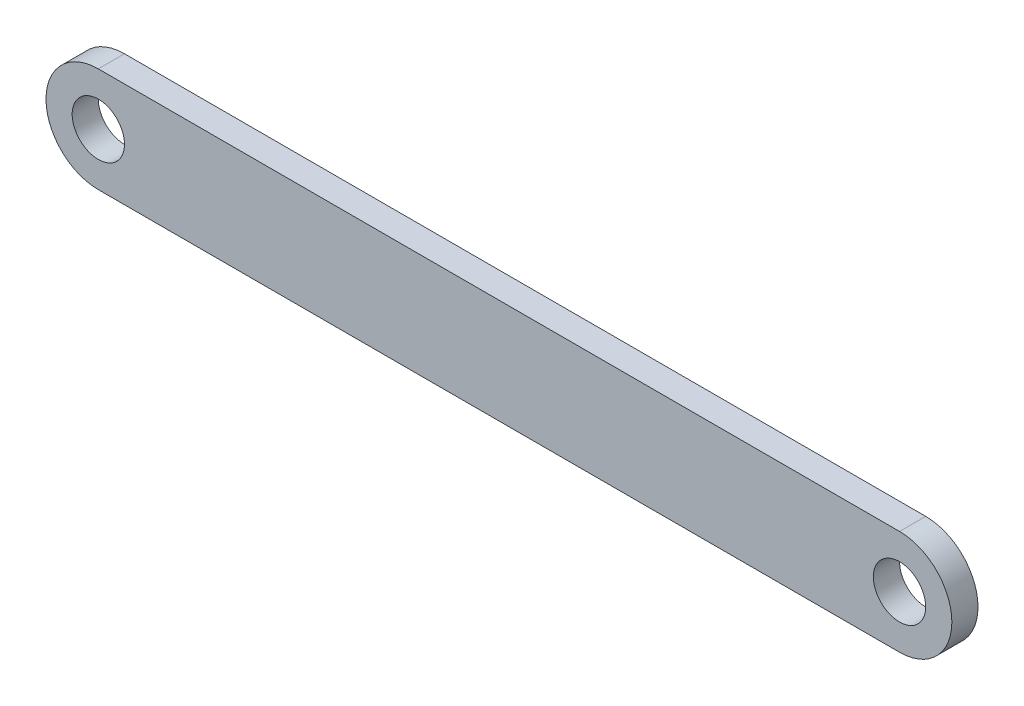
SolidWorks part; units mm, degrees
ref_plane "Plano frontal" through (0, 0, 0) normal (0, 0, 1) x (1, 0, 0)
ref_plane "Plano superior" through (0, 0, 0) normal (0, 1, 0) x (1, 0, 0)
ref_plane "Plano direito" through (0, 0, 0) normal (1, 0, 0) x (0, 0, -1)
sketch "Esboço1" plane through (0, 0, 0) normal (0, 0, 1) x (1, 0, 0)
  line L0 (-15.315, 2) -> (15.315, 2)
  line L1 (-15.315, 0) -> (15.315, 0) construction
  line L2 (-15.315, -2) -> (15.315, -2)
  arc A0 (-15.315, 2) -> (-15.315, -2) centre (-15.315, 0) ccw
  arc A1 (15.315, 2) -> (15.315, -2) centre (15.315, 0) cw
  circle A2 centre (-15.315, 0) radius 1
  circle A3 centre (15.315, 0) radius 1
  point P3 (0, 2)
  dimension "D2" = 2
  dimension "D1" = 30.63
extrude "Ressalto-extrusão1" add sketch "Esboço1" along normal blind 1
